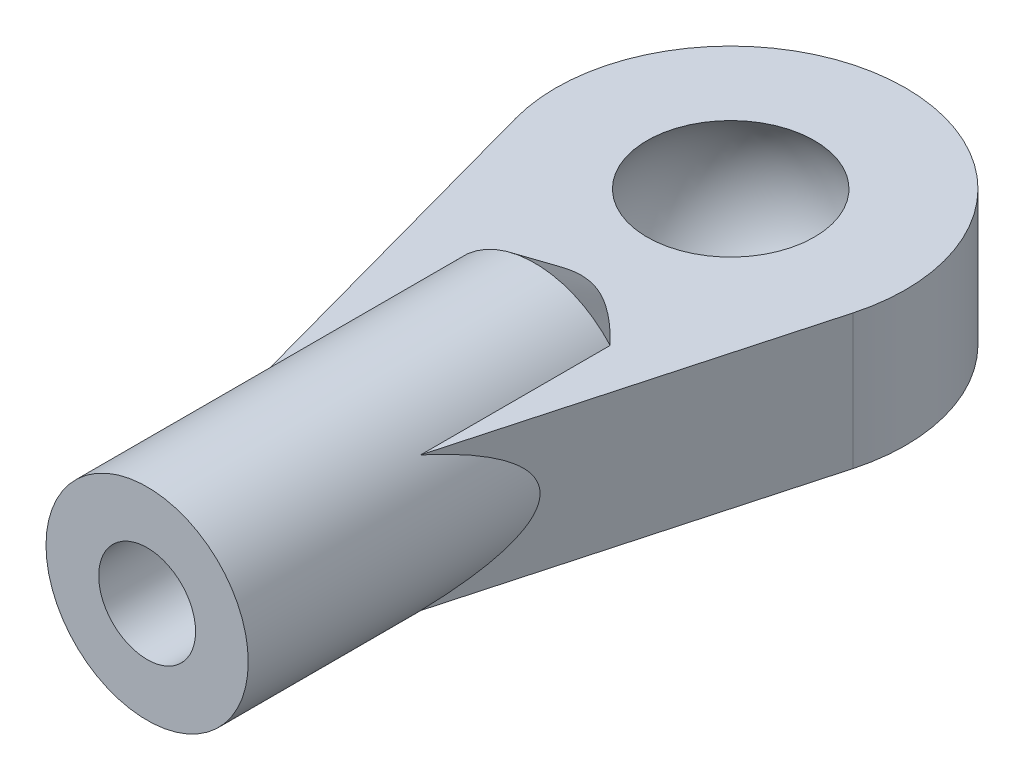
SolidWorks part; units mm, degrees
material "Custom Plastic"
ref_plane "Front Plane" through (0, 0, 0) normal (0, 0, 1) x (1, 0, 0)
ref_plane "Top Plane" through (0, 0, 0) normal (0, 1, 0) x (1, 0, 0)
ref_plane "Right Plane" through (0, 0, 0) normal (1, 0, 0) x (0, 0, -1)
sketch "Sketch1" plane through (0, 0, 0) normal (0, 0, 1) x (1, 0, 0)
  line L0 (0, 0) -> (0, 1.6) construction
  line L1 (0, 1.6) -> (1.9856, 1.6) construction
  line L2 (2.55, 0) -> (4.15, 0) construction
  line L3 (1.9856, 1.6) -> (4.15, 1.6)
  line L4 (4.15, 1.6) -> (4.15, -1.6)
  line L5 (1.9856, -1.6) -> (4.15, -1.6)
  circle A0 centre (0, 0) radius 2.55 construction
  arc A1 (1.9856, 1.6) -> (1.9856, -1.6) centre (0, 0) cw
  dimension "D1" = 5.1
  dimension "D2" = 1.6
  dimension "D3" = 1.6
revolve "Revolve1" add sketch "Sketch1" angle 360 about L0
sketch "Sketch2" plane through (0, 1.6, 0) normal (0, 1, 0) x (1, 0, 0)
  line L0 (-2.4, -6.925) -> (-4.0015, -1.1002)
  line L1 (0, 0) -> (0, -13.85) construction
  line L2 (-2.4, -13.85) -> (2.4, -13.85)
  line L3 (2.4, -6.925) -> (4.0015, -1.1002)
  line L4 (-2.4, -6.925) -> (-2.4, -13.85)
  line L5 (2.4, -6.925) -> (2.4, -13.85)
  circle A1 centre (0, 0) radius 4.15 construction
  circle A2 centre (0, 0) radius 4.15 construction
  arc A3 (-4.0015, -1.1002) -> (4.0015, -1.1002) centre (0, 0) ccw
  point P11 (0, -13.85)
  point P12 (0, -6.925)
  dimension "D1" = 13.85
  dimension "D2" = 4.8
extrude "Boss-Extrude1" add sketch "Sketch2" against normal blind 3.2
sketch "Sketch3" plane through (0, 0, 13.85) normal (0, 0, 1) x (1, 0, 0)
  circle A0 centre (0, 0) radius 2.4
extrude "Boss-Extrude2" add sketch "Sketch3" against normal blind 9.2
sketch "Sketch4" plane through (0, 0, 4.65) normal (0, 0, -1) x (-1, 0, 0)
  circle A0 centre (0, 0) radius 2.4
  arc A1 (1.7889, 1.6) -> (-1.7889, 1.6) centre (0, 0) ccw construction
extrude "Boss-Extrude3" add sketch "Sketch4" along normal blind 1.2 draft 36
sketch "Sketch5" plane through (0, 0, 13.85) normal (0, 0, 1) x (1, 0, 0)
  line L0 (1.7889, 1.6) -> (2.4, 1.6)
  line L1 (2.4, 1.6) -> (2.4, 0)
  line L2 (2.4, 0) -> (2.4, -1.6)
  line L3 (2.4, -1.6) -> (1.7889, -1.6)
  line L4 (1.7889, -1.6) -> (2.4, -1.6) construction
  line L5 (0, 0) -> (0, 1) construction
  line L6 (-2.4, -1.6) -> (-1.7889, -1.6)
  line L7 (-2.4, 0) -> (-2.4, -1.6)
  line L8 (-2.4, 1.6) -> (-2.4, 0)
  line L9 (-1.7889, 1.6) -> (-2.4, 1.6)
  arc A0 (1.7889, -1.6) -> (1.7889, 1.6) centre (0, 0) ccw
  arc A1 (1.7889, 1.6) -> (-1.7889, 1.6) centre (0, 0) ccw construction
  arc A2 (-1.7889, -1.6) -> (-1.7889, 1.6) centre (0, 0) cw
  line M7 (2.4, -1.6) -> (2.4, 1.6)
  line M8 (2.4, 1.6) -> (1.7889, 1.6)
  line M10 (-1.7889, 1.6) -> (-2.4, 1.6)
  line M11 (-2.4, 1.6) -> (-2.4, -1.6)
  line M12 (-2.4, -1.6) -> (-1.7889, -1.6)
  line M14 (1.7889, -1.6) -> (2.4, -1.6)
  dimension "D1" = 1
extrude "Cut-Extrude1" cut sketch "Sketch5" against normal up to vertex (6.925 mm away) contours A0 M7 M8 | A0 M14 M7 | A2 M11 M10 | A2 M12 M11
sketch "Sketch6" plane through (0, 1.6, 0) normal (0, 1, 0) x (1, 0, 0)
  line L0 (-2.4, -6.925) -> (-1, -12.0169)
  line L1 (-4.0015, -1.1002) -> (-2.4, -6.925) construction
  line L2 (-1, -12.0169) -> (1, -12.0169)
  line L3 (0, -6.925) -> (0, -3.7892) construction
  line L4 (-2.4, -6.925) -> (2.4, -6.925)
  line L5 (2.4, -6.925) -> (1, -12.0169)
  point P14 (0, -12.0169)
  dimension "D1" = 1
extrude "Boss-Extrude4" add sketch "Sketch6" against normal up to vertex (3.2 mm away)
hole_wizard "Tap Drill for M2.2 Helicoil1" positions "Sketch10" profile "Sketch12" hole size "M2.2x0.45" standard "ANSI Metric"
sketch "Sketch10" plane through (0, 0, 13.85) normal (0, 0, 1) x (1, 0, 0)
  point P0 (0, 0)
sketch "Sketch12" plane through (0, 0, 13.85) normal (1, 0, 0) x (0, -1, 0)
  line L0 (0, 0) -> (0, 9.891)
  line L1 (0, 9.891) -> (1.15, 9.2)
  line L2 (1.15, 9.2) -> (1.15, 0)
  line L5 (1.15, 0) -> (0, 0)
  line L10 (0, 9.891) -> (-1.15, 9.2) construction
  line L11 (0, -6.35) -> (0, 107.95) construction
  dimension "Hole Dia." = 2.3
  dimension "Hole Depth" = 9.2
  dimension "Drill Angle" = 118
ref_point "Point1"
